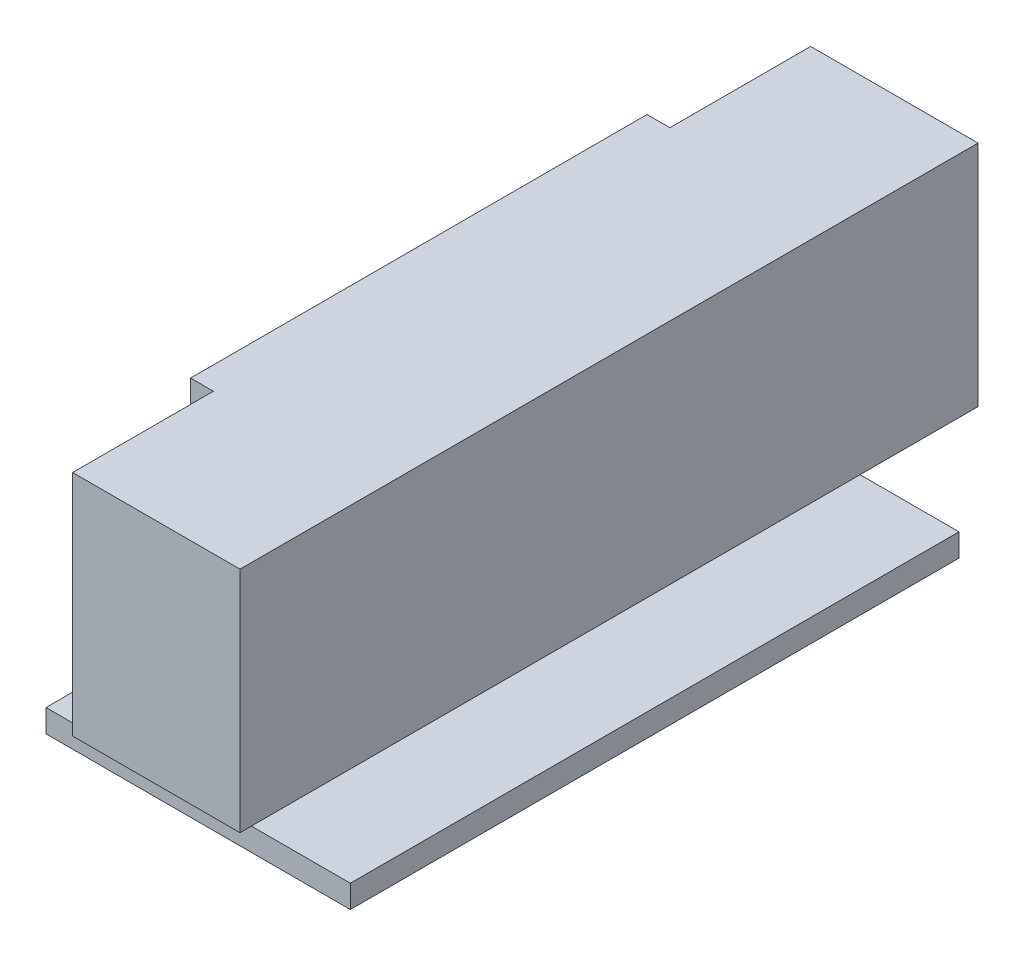
SolidWorks part; units mm, degrees
ref_plane "Front Plane" through (0, 0, 0) normal (0, 0, 1) x (1, 0, 0)
ref_plane "Top Plane" through (0, 0, 0) normal (0, 1, 0) x (1, 0, 0)
ref_plane "Right Plane" through (0, 0, 0) normal (1, 0, 0) x (0, 0, -1)
sketch "SK_Bracket_Base" plane through (0, 0, 0) normal (0, 0, 1) x (1, 0, 0)
  line L0 (-23, 0) -> (17, 0)
  line L1 (17, 0) -> (17, 3)
  line L2 (17, 3) -> (-23, 3)
  line L3 (-23, 3) -> (-23, 0)
extrude "Bracket_Base" add sketch "SK_Bracket_Base" along normal mid plane 80
sketch "SK_Bracket_Upright" plane through (0, 0, 0) normal (0, 0, 1) x (1, 0, 0)
  line L0 (-14, 0) -> (-11, 0)
  line L1 (-11, 0) -> (-11, 40)
  line L2 (-11, 40) -> (-14, 40)
  line L3 (-14, 40) -> (-14, 0)
extrude "Bracket_Upright" add sketch "SK_Bracket_Upright" along normal mid plane 60
sketch "SK_Camera" plane through (0, 0, 0) normal (0, 0, 1) x (1, 0, 0)
  line L0 (-11, 10) -> (11, 10)
  line L1 (11, 10) -> (11, 40)
  line L2 (11, 40) -> (-11, 40)
  line L3 (-11, 40) -> (-11, 10)
extrude "Camera" add sketch "SK_Camera" along normal mid plane 97
